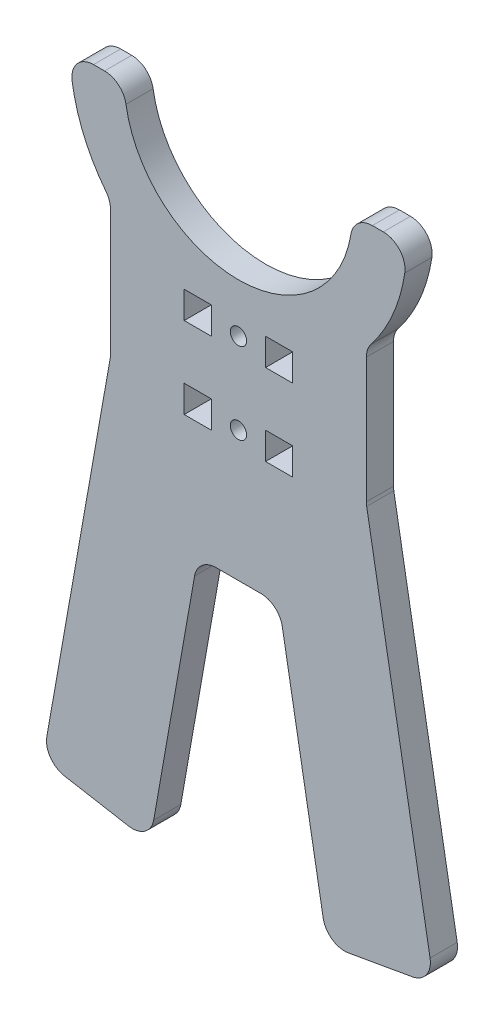
SolidWorks part; units mm, degrees
ref_plane "Front Plane" through (0, 0, 0) normal (0, 0, 1) x (1, 0, 0)
ref_plane "Top Plane" through (0, 0, 0) normal (0, 1, 0) x (1, 0, 0)
ref_plane "Right Plane" through (0, 0, 0) normal (1, 0, 0) x (0, 0, -1)
sketch "Sketch1" plane through (0, 0, 0) normal (0, 0, 1) x (1, 0, 0)
  line L0 (0, 0) -> (0, 60.0775) construction
  line L1 (0, 0) -> (83.5659, 0) construction
  line L2 (-21, 45) -> (-31, 45)
  line L3 (21, 45) -> (31, 45)
  line L4 (-23.5767, 24.8719) -> (-23.5767, 0)
  line L5 (-23.5767, 0) -> (-36.0125, -70.527)
  line L6 (-36.0125, -70.527) -> (-16.3163, -74)
  line L7 (-16.3163, -74) -> (-7.5, -24)
  line L8 (-7.5, -24) -> (7.5, -24)
  line L9 (7.5, -24) -> (16.3163, -74)
  line L10 (16.3163, -74) -> (36.0125, -70.527)
  line L11 (36.0125, -70.527) -> (23.5767, 0)
  line L12 (23.5767, 0) -> (23.5767, 24.8719)
  arc A0 (-21, 45) -> (21, 45) centre (0, 45) ccw
  arc A1 (23.5767, 24.8719) -> (31, 45) centre (0, 45) ccw
  arc A2 (-31, 45) -> (-23.5767, 24.8719) centre (0, 45) ccw
  point P5 (0, 41.5337)
  point P11 (0, 0)
  point P20 (0, 0)
  point P21 (0, 0)
  point P22 (0, 0)
  point P23 (0, 0)
  line B0 (-5, 2.5) -> (-10, 2.5)
  line B1 (-5, 2.5) -> (-5, -2.5)
  line B2 (-5, -2.5) -> (-10, -2.5)
  line B3 (-10, 2.5) -> (-10, -2.5)
  line B4 (5, 2.5) -> (10, 2.5)
  line B5 (5, 2.5) -> (5, -2.5)
  line B6 (5, -2.5) -> (10, -2.5)
  line B7 (10, 2.5) -> (10, -2.5)
  circle B8 centre (0, 0) radius 1.5
  line B9 (-5, 17.5) -> (-10, 17.5)
  line B10 (-5, 17.5) -> (-5, 12.5)
  line B11 (-5, 12.5) -> (-10, 12.5)
  line B12 (-10, 17.5) -> (-10, 12.5)
  line B13 (5, 17.5) -> (10, 17.5)
  line B14 (5, 17.5) -> (5, 12.5)
  line B15 (5, 12.5) -> (10, 12.5)
  line B16 (10, 17.5) -> (10, 12.5)
  circle B17 centre (0, 15) radius 1.5
  dimension "D1" = 42
  dimension "D2" = 62
  dimension "D3" = 45
  dimension "D4" = 15
  dimension "D5" = 24
  dimension "D6" = 20
  dimension "D7" = 50
  dimension "D8" = 20
  dimension "D9" = 30
  dimension "D10" = 32.6327
sketch_block_instance "Trou M3 plots 5mm-1"
sketch_block "Trou M3 plots 5mm" parameters "D2"=3, "D1"=5, "D3"=5, "D4"=10
sketch_block_instance "Trou M3 plots 5mm-3"
extrude "Boss-Extrude1" add sketch "Sketch1" along normal blind 5
fillet "Fillet1" radius 4 14 edges at (23.5767, 24.8719, 2.5) (-23.5767, 24.8719, 2.5) (-23.5767, 0, 2.5) (23.5767, 0, 2.5) (-36.0125, -70.527, 2.5) (-16.3163, -74, 2.5) (16.3163, -74, 2.5) (36.0125, -70.527, 2.5) (7.5, -24, 2.5) (-7.5, -24, 2.5) (31, 45, 2.5) (21, 45, 2.5) (-31, 45, 2.5) (-21, 45, 2.5)
